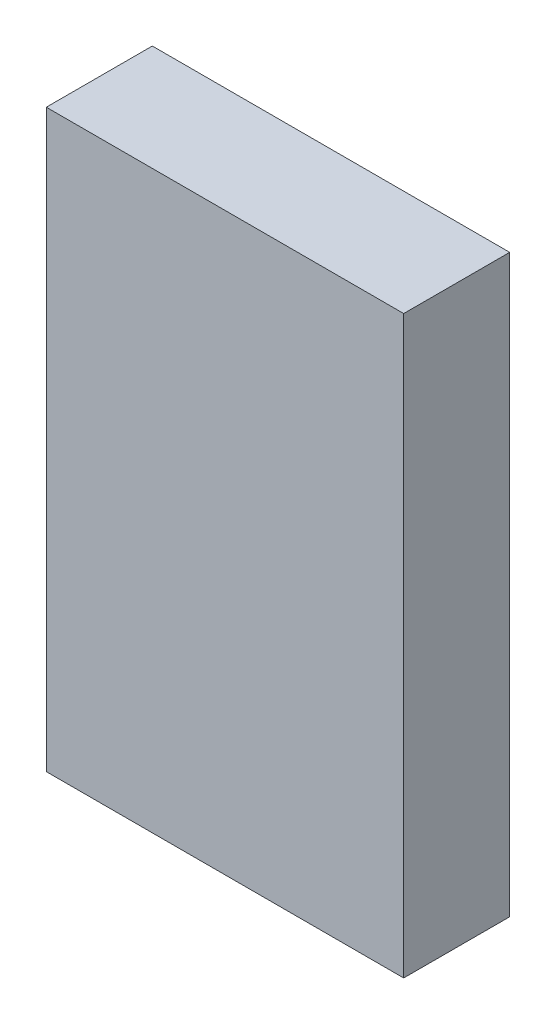
SolidWorks part; units mm, degrees
material "Zinc AC43A (Zn-4Al-2.5Cu-0.04Mg; Number 2 Die Casting Alloy; Zamak 2), Die Cast"
ref_plane "Front Plane" through (0, 0, 0) normal (0, 0, 1) x (1, 0, 0)
ref_plane "Top Plane" through (0, 0, 0) normal (0, 1, 0) x (1, 0, 0)
ref_plane "Right Plane" through (0, 0, 0) normal (1, 0, 0) x (0, 0, -1)
sketch "Sketch1" plane through (0, 0, 0) normal (0, 0, 1) x (1, 0, 0)
  line L1 (5.9, -9.5) -> (-5.9, -9.5)
  line L2 (5.9, -9.5) -> (5.9, 9.5)
  line L3 (5.9, 9.5) -> (-5.9, 9.5)
  line L4 (-5.9, -9.5) -> (-5.9, 9.5)
  line L5 (5.9, -9.5) -> (-5.9, 9.5) construction
  line L6 (5.9, 9.5) -> (-5.9, -9.5) construction
  point P0 (0, 0)
  dimension "D1" = 19
  dimension "D2" = 11.8
extrude "Boss-Extrude1" add sketch "Sketch1" along normal mid plane 3.5
